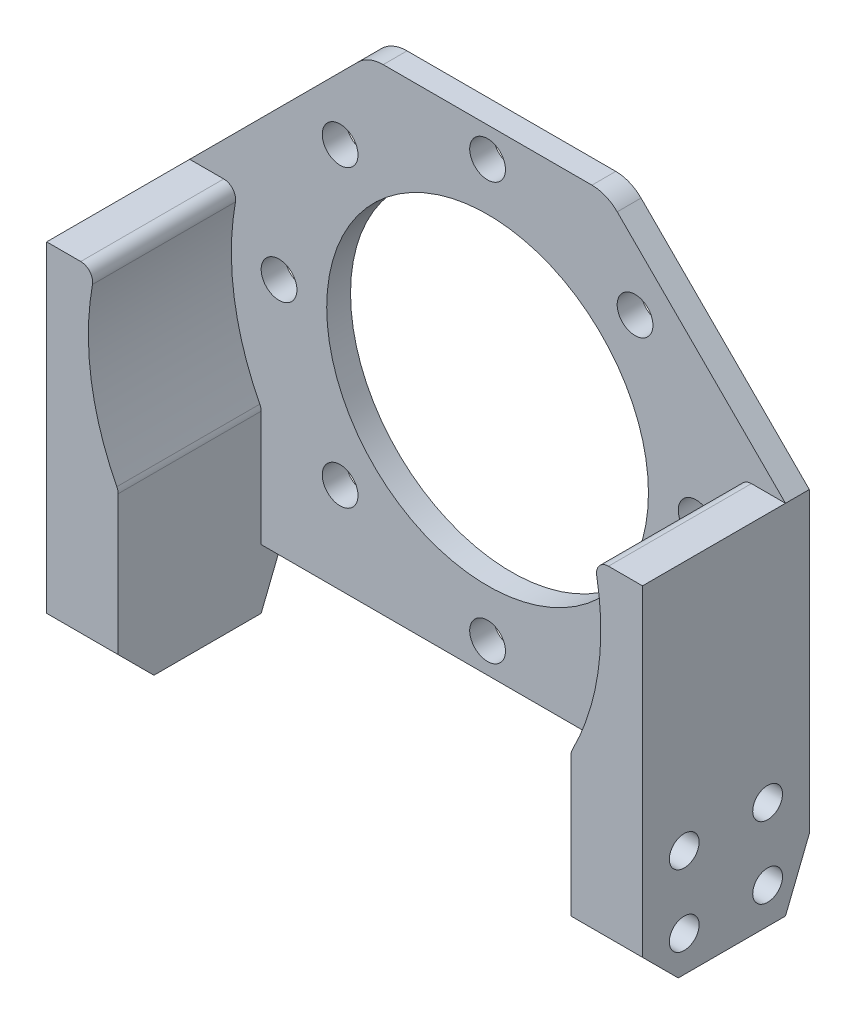
SolidWorks part; units mm, degrees
material "6061-T4 (SS)"
ref_plane "前视基准面" through (0, 0, 0) normal (0, 0, 1) x (1, 0, 0)
ref_plane "上视基准面" through (0, 0, 0) normal (0, 1, 0) x (1, 0, 0)
ref_plane "右视基准面" through (0, 0, 0) normal (1, 0, 0) x (0, 0, -1)
other "Configuration Table"
sketch "草图1" plane through (0, 0, 0) normal (0, 0, 1) x (1, 0, 0)
  line L1 (-25, -25) -> (25, -25)
  line L2 (-25, -25) -> (-25, 25)
  line L3 (-25, 25) -> (25, 25)
  line L4 (25, -25) -> (25, 25)
  line L5 (-25, -25) -> (25, 25) construction
  line L6 (-25, 25) -> (25, -25) construction
  circle A0 centre (0, 0) radius 13.5
  circle A1 centre (0, 0) radius 17.5 construction
  circle A2 centre (0, 17.5) radius 1.5
  circle A3 centre (12.3744, 12.3744) radius 1.5
  circle A4 centre (17.5, 0) radius 1.5
  circle A5 centre (12.3744, -12.3744) radius 1.5
  circle A6 centre (0, -17.5) radius 1.5
  circle A7 centre (-12.3744, -12.3744) radius 1.5
  circle A8 centre (-17.5, 0) radius 1.5
  circle A9 centre (-12.3744, 12.3744) radius 1.5
  circle A10 centre (0, 0) radius 21.5
  point P0 (0, 0)
  point P27 (0, 0)
  dimension "D1" = 35
  dimension "D2" = 27
  dimension "D3" = 3
  dimension "D5" = 43
  dimension "D6" = 50
  dimension "D4" = 8
extrude "凸台-拉伸1" add sketch "草图1" along normal blind 8 contours L1 L4 L3 L2 A10 | A10 A0 A2 A3 A4 A5 A6 A7 A8 A9 | A0
sketch "草图2" plane through (0, 0, 8) normal (0, 0, 1) x (1, 0, 0)
  circle A0 centre (0, 0) radius 21.5
  dimension "D1" = 43
extrude "切除-拉伸1" cut sketch "草图2" against normal blind 6
sketch "草图3" plane through (0, 0, 8) normal (0, 0, 1) x (1, 0, 0)
  line L0 (25, -25) -> (25, 25) construction
  line L1 (-25, 25) -> (25, 25)
  line L2 (-25, 25) -> (-25, 20)
  line L3 (-25, 20) -> (25, 20)
  line L4 (25, 25) -> (25, 20)
  dimension "D1" = 5
extrude "切除-拉伸2" cut sketch "草图3" against normal blind 27
sketch "草图4" plane through (0, 0, 8) normal (0, 0, 1) x (1, 0, 0)
  line L0 (-25, 5) -> (-25, 20)
  line L1 (-25, -25) -> (-25, 20) construction
  line L2 (-25, 20) -> (-10, 20)
  line L3 (-25, 20) -> (-7.8899, 20) construction
  line L4 (-10, 20) -> (-25, 5)
  line L5 (0, 0) -> (0, 28.7721) construction
  line L6 (10, 20) -> (25, 5)
  line L7 (25, 20) -> (10, 20)
  line L8 (25, 5) -> (25, 20)
  dimension "D1" = 15
  dimension "D2" = 15
extrude "切除-拉伸3" cut sketch "草图4" against normal blind 10
sketch "草图5" plane through (0, 0, 8) normal (0, 0, 1) x (1, 0, 0)
  line L0 (7.8899, 20) -> (10, 20) construction
  line L1 (-30.2595, 20) -> (29.6899, 20)
  line L2 (-30.2595, 20) -> (-30.2595, 5)
  line L3 (-30.2595, 5) -> (29.6899, 5)
  line L4 (29.6899, 20) -> (29.6899, 5)
  dimension "D1" = 15
extrude "切除-拉伸4" cut sketch "草图5" against normal blind 6
sketch "草图6" plane through (0, 0, 2) normal (0, 0, 1) x (1, 0, 0)
  circle A0 centre (0, 0) radius 13.5
  dimension "D1" = 27
extrude "切除-拉伸5" cut sketch "草图6" against normal blind 10
sketch "草图7" plane through (0, 0, 8) normal (0, 0, 1) x (1, 0, 0)
  line L0 (0, 0) -> (0, -29.7548) construction
  line L1 (25, -25) -> (25, 5) construction
  line L2 (-19, -35.7338) -> (19, -35.7338)
  line L3 (-19, -35.7338) -> (-19, -10.0623)
  line L4 (-19, -10.0623) -> (19, -10.0623)
  line L5 (19, -35.7338) -> (19, -10.0623)
  line L6 (-19, -35.7338) -> (19, -10.0623) construction
  line L7 (-19, -10.0623) -> (19, -35.7338) construction
  arc A0 (-20.9105, 5) -> (20.9105, 5) centre (0, 0) ccw construction
  point P3 (0, -22.898)
  dimension "D1" = 6
extrude "切除-拉伸6" cut sketch "草图7" against normal blind 6
sketch "草图8" plane through (0, 0, 8) normal (0, 0, 1) x (1, 0, 0)
  line L0 (19, -10.0623) -> (19, -25) construction
  line L1 (19, -25) -> (25, -25) construction
  line L2 (25, -25) -> (25, 5) construction
  line L3 (25, 5) -> (20.9105, 5) construction
  line L4 (-19, -25) -> (-19, -10.0623) construction
  line L5 (-20.9105, 5) -> (-25, 5) construction
  line L6 (-25, 5) -> (-25, -25) construction
  line L7 (-25, -25) -> (-19, -25) construction
  line L8 (19, -10.0623) -> (19, -25)
  line L9 (19, -25) -> (25, -25)
  line L10 (25, -25) -> (25, 5)
  line L11 (25, 5) -> (20.9105, 5)
  line L12 (-19, -25) -> (-19, -10.0623)
  line L13 (-20.9105, 5) -> (-25, 5)
  line L14 (-25, 5) -> (-25, -25)
  line L15 (-25, -25) -> (-19, -25)
  arc A0 (19, -10.0623) -> (20.9105, 5) centre (0, 0) ccw construction
  arc A1 (-20.9105, 5) -> (-19, -10.0623) centre (0, 0) ccw construction
  arc A2 (19, -10.0623) -> (20.9105, 5) centre (0, 0) ccw
  arc A3 (-20.9105, 5) -> (-19, -10.0623) centre (0, 0) ccw
extrude "凸台-拉伸2" add sketch "草图8" along normal blind 6
sketch "草图9" plane through (25, 0, 0) normal (1, 0, 0) x (0, 0, -1)
  line L0 (0, -25) -> (0, 5) construction
  line L1 (-10.5, -16) -> (-3.5, -16) construction
  line L2 (-10.5, -16) -> (-10.5, -22) construction
  line L3 (-10.5, -22) -> (-3.5, -22) construction
  line L4 (-3.5, -16) -> (-3.5, -22) construction
  line L6 (-14, -25) -> (0, -25) construction
  circle A0 centre (-3.5, -16) radius 1.25
  circle A1 centre (-3.5, -22) radius 1.25
  circle A2 centre (-10.5, -16) radius 1.25
  circle A3 centre (-10.5, -22) radius 1.25
  dimension "D1" = 2.5
  dimension "D2" = 7
  dimension "D3" = 3.5
  dimension "D4" = 3
  dimension "D5" = 6
extrude "切除-拉伸7" cut sketch "草图9" against normal blind 5
mirror "镜向1" about plane through (0, 0, 0) normal (1, 0, 0) of "切除-拉伸7"
fillet "圆角1" radius 1 4 edges at (-19, -10.0623, 8) (-20.9105, 5, 8) (19, -10.0623, 8) (20.9105, 5, 8)
fillet "圆角2" radius 3 2 edges at (10, 20, 1) (-10, 20, 1)
chamfer "倒角1" distance 3 angle 45 2 edges at (22, -25, 14) (-22, -25, 14)
sketch "草图10" plane through (25, 0, 0) normal (1, 0, 0) x (0, 0, -1)
  line L0 (-2, -25) -> (0, -25)
  line L1 (-11, -25) -> (0, -25) construction
  line L2 (0, 24.75) -> (0, -24.75) construction
  line L3 (0, -25) -> (0, -20)
  line L4 (0, -20) -> (-2, -25)
  dimension "D1" = 2
  dimension "D2" = 5
extrude "切除-拉伸8" cut sketch "草图10" against normal blind 51
sketch "草图11" plane through (19, 0, 0) normal (-1, 0, 0) x (0, 0, 1)
  line L0 (2, -25) -> (2, -20)
  line L1 (2, -20) -> (0, -20)
  line L2 (0, -24.75) -> (0, 24.75) construction
  line L3 (2, -25) -> (0, -20) construction
  line L5 (2, -25) -> (0, -20)
extrude "切除-拉伸9" cut sketch "草图11" along normal up to surface (38 mm away) up to face at (-19, -18.5231, 8.6)
